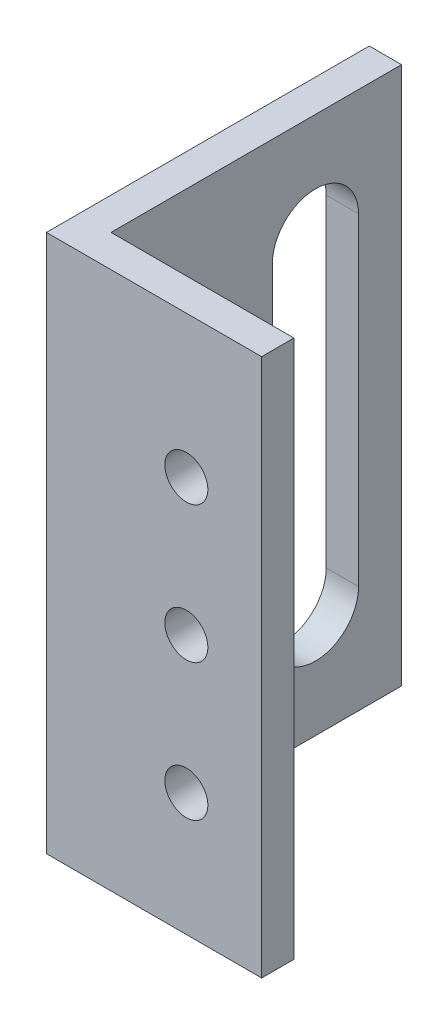
SolidWorks part; units mm, degrees
ref_plane "前视基准面" through (0, 0, 0) normal (0, 0, 1) x (1, 0, 0)
ref_plane "上视基准面" through (0, 0, 0) normal (0, 1, 0) x (1, 0, 0)
ref_plane "右视基准面" through (0, 0, 0) normal (1, 0, 0) x (0, 0, -1)
sketch "草图1" plane through (0, 0, 0) normal (0, 1, 0) x (1, 0, 0)
  line L2 (-1.5, 15) -> (1.5, 15)
  line L3 (-1.5, 15) -> (-1.5, -15)
  line L4 (-1.5, -15) -> (1.5, -15)
  line L5 (1.5, 15) -> (1.5, -15)
  line L6 (-1.5, 15) -> (1.5, -15) construction
  line L7 (-1.5, -15) -> (1.5, 15) construction
  line L8 (-1.5, -15) -> (18.5, -15)
  line L9 (-1.5, -15) -> (-1.5, -12)
  line L10 (-1.5, -12) -> (18.5, -12)
  line L11 (18.5, -15) -> (18.5, -12)
  point P2 (0, 0)
  dimension "D1" = 3
  dimension "D2" = 3
  dimension "D3" = 30
  dimension "D4" = 20
extrude "凸台-拉伸1" add sketch "草图1" along normal blind 50 contours L3 L10 L5 L2 | L10 L3 L4 L5 | L8 L11 L10 L5
sketch "草图2" plane through (0, 0, 15) normal (0, 0, 1) x (1, 0, 0)
  line L0 (11.5, 50) -> (11.5, 0) construction
  line L1 (-1.5, 50) -> (18.5, 50) construction
  line L3 (18.5, 50) -> (18.5, 0) construction
  circle A0 centre (11.5, 36.8) radius 2
  circle A2 centre (11.5, 24.1) radius 2
  circle A3 centre (11.5, 11.4) radius 2
  dimension "D1" = 4
  dimension "D2" = 13.2
  dimension "D4" = 12.7
  dimension "D5" = 7
  dimension "D3" = 3
extrude "切除-拉伸1" cut sketch "草图2" against normal blind 10
sketch "草图3" plane through (-1.5, 0, 0) normal (-1, 0, 0) x (0, 0, 1)
  line L0 (-7, 40) -> (-7, 10) construction
  line L1 (-3, 40) -> (-3, 10)
  line L2 (-11, 40) -> (-11, 10)
  line L4 (-15, 50) -> (-15, 0) construction
  line L5 (-15, 25) -> (15, 25) construction
  line L6 (15, 50) -> (15, 0) construction
  arc A0 (-3, 40) -> (-11, 40) centre (-7, 40) ccw
  arc A1 (-11, 10) -> (-3, 10) centre (-7, 10) ccw
  point P3 (-7, 25)
  dimension "D3" = 4
  dimension "D1" = 30
  dimension "D2" = 8
extrude "切除-拉伸2" cut sketch "草图3" against normal blind 10
